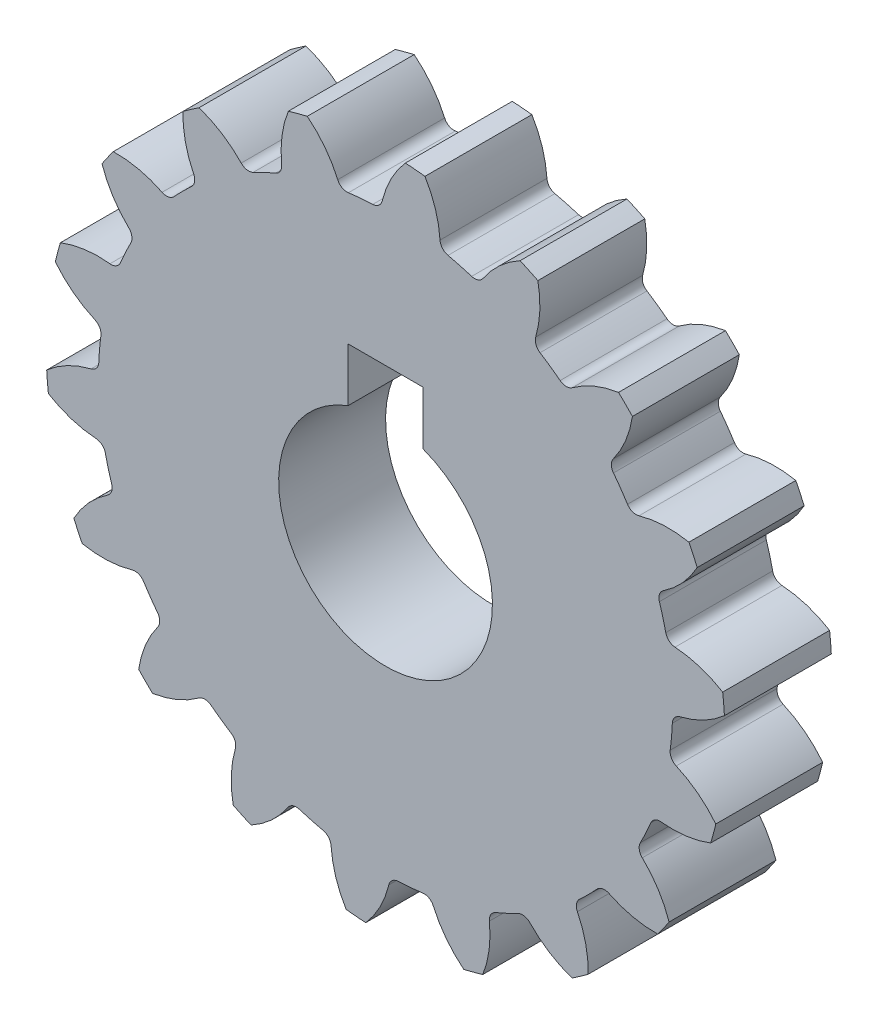
SolidWorks part; units mm, degrees
ref_plane "Alzado" through (0, 0, 0) normal (0, 0, 1) x (1, 0, 0)
ref_plane "Planta" through (0, 0, 0) normal (0, 1, 0) x (1, 0, 0)
ref_plane "Vista lateral" through (0, 0, 0) normal (1, 0, 0) x (0, 0, -1)
sketch "Croquis1" plane through (0, 0, 0) normal (0, 0, 1) x (1, 0, 0)
  line L0 (0, 0) -> (0, 31.75) construction
  line L1 (0, 28.575) -> (9.1838, 25.2324) construction
  line L2 (0, 0) -> (2.7707, 31.6289) construction
  line L3 (4.9683, 28.1398) -> (-4.6569, 26.4448) construction
  circle A1 centre (0, 0) radius 24.8698 construction
  circle A2 centre (0, 0) radius 28.575 construction
  circle A3 centre (0, 0) radius 31.75 construction
  circle A4 centre (0, 0) radius 26.8517 construction
  arc A5 (1.8531, 31.6959) -> (-0.455, 26.8479) centre (9.1838, 25.2324) ccw
  arc A6 (3.686, 31.5353) -> (5.116, 26.3598) centre (-4.6569, 26.4448) cw
  dimension "df" = 49.7396
  dimension "dp" = 57.15
  dimension "de" = 63.5
  dimension "db" = 53.7034
  dimension "angulo_paso" = 20
  dimension "s" = 4.9873
sketch "Croquis2" plane through (0, 0, 0) normal (0, 0, 1) x (1, 0, 0)
  circle A0 centre (0, 0) radius 26.8517 construction
  arc A1 (5.116, 26.3598) -> (3.686, 31.5353) centre (-4.6569, 26.4448) ccw construction
  arc A2 (1.8531, 31.6959) -> (-0.455, 26.8479) centre (9.1838, 25.2324) ccw construction
  circle A3 centre (0, 0) radius 31.75 construction
  arc A4 (-0.455, 26.8479) -> (5.116, 26.3598) centre (0, 0) ccw
  arc A5 (5.116, 26.3598) -> (3.686, 31.5353) centre (-4.6569, 26.4448) ccw
  arc A6 (1.8531, 31.6959) -> (-0.455, 26.8479) centre (9.1838, 25.2324) ccw
  arc A7 (3.686, 31.5353) -> (1.8531, 31.6959) centre (0, 0) ccw
extrude "Saliente-Extruir1" add sketch "Croquis2" along normal blind 10
fillet "Redondeo1" radius 0.9525 2 edges at (-0.455, 26.8479, 5) (5.116, 26.3598, 5)
pattern_circular "MatrizC1" count 18 over 360 about axis through (0, 0, 0) along (0, 0, 1) of "Saliente-Extruir1", "Redondeo1"
sketch "Croquis3" plane through (0, 0, 10) normal (0, 0, 1) x (1, 0, 0)
  line L1 (-3.5, 14.3675) -> (3.5, 14.3675)
  line L2 (-3.5, 14.3675) -> (-3.5, 9.3675)
  line L4 (3.5, 14.3675) -> (3.5, 9.3675)
  arc A0 (-3.5, 9.3675) -> (3.5, 9.3675) centre (0, 0) ccw
  dimension "D1" = 20
  dimension "D2" = 7
  dimension "D3" = 5
extrude "Cortar-Extruir2" cut sketch "Croquis3" against normal up to next
equation "\"m\"= 3.175"
equation "\"Ze\"= 18"
equation "\"ϕ\"= 20"
equation "\"dp@Croquis1\" = \"m\" * \"Ze\""
equation "\"db@Croquis1\" = \"dp@Croquis1\" * cos ( \"ϕ\" ) "
equation "\"s@Croquis1\"= \"m\" * ( 3.1415926535897932384626433832795 / 2 )"
equation "\"de@Croquis1\"= \"dp@Croquis1\" + ( \"m\" * 2 )"
equation "\"df@Croquis1\" = \"dp@Croquis1\" - ( \"m\" * 2.334 )"
equation "\"D1@Redondeo1\"=\"m\"*0.3"
equation "\"D1@MatrizC1\"=\"Ze\""
